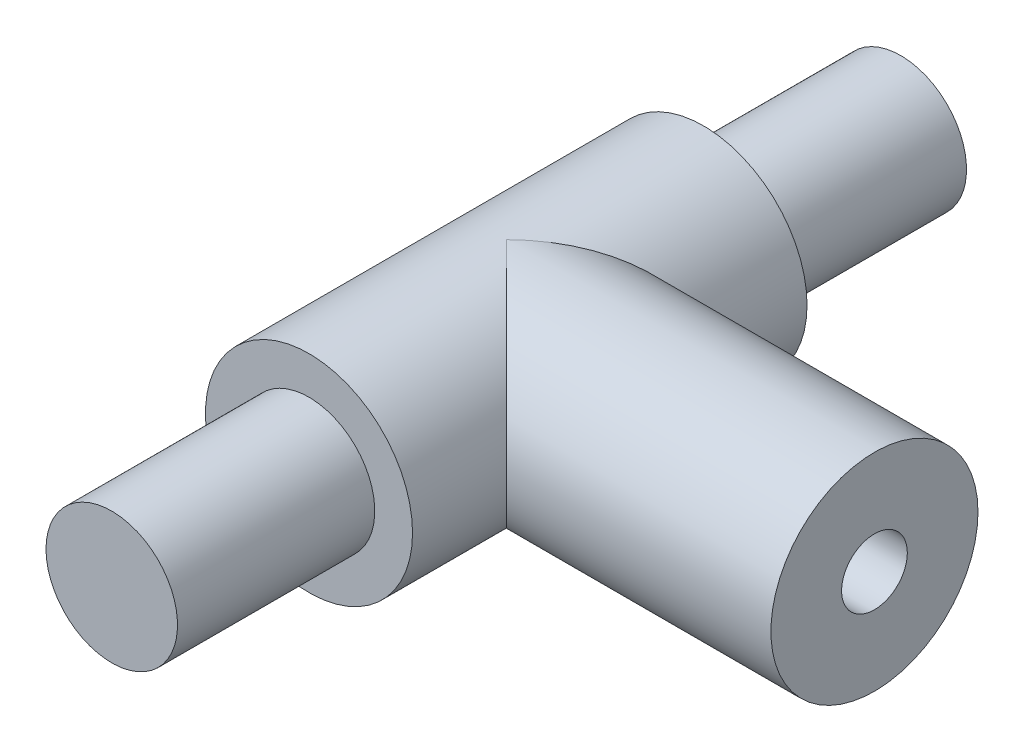
SolidWorks part; units mm, degrees
ref_plane "Front Plane" through (0, 0, 0) normal (0, 0, 1) x (1, 0, 0)
ref_plane "Top Plane" through (0, 0, 0) normal (0, 1, 0) x (1, 0, 0)
ref_plane "Right Plane" through (0, 0, 0) normal (1, 0, 0) x (0, 0, -1)
sketch "Sketch1" plane through (0, 0, 0) normal (0, 0, 1) x (1, 0, 0)
  circle A0 centre (0, 0) radius 5
  dimension "D1" = 10
extrude "Boss-Extrude1" add sketch "Sketch1" along normal mid plane 19.05
sketch "Sketch5" plane through (0, 0, 0) normal (0, 0, 1) x (1, 0, 0)
  circle A0 centre (0, 0) radius 3.175
  dimension "D1" = 6.35
extrude "Boss-Extrude4" add sketch "Sketch5" along normal mid plane 38.1
sketch "Sketch6" plane through (0, 0, 0) normal (1, 0, 0) x (0, 0, -1)
  circle A0 centre (0, 0) radius 5
  dimension "D1" = 10
extrude "Boss-Extrude5" add sketch "Sketch6" along normal blind 17.78
sketch "Sketch7" plane through (17.78, 0, 0) normal (1, 0, 0) x (0, 0, -1)
  circle A0 centre (0, 0) radius 1.5875
  dimension "D1" = 3.175
extrude "Cut-Extrude1" cut sketch "Sketch7" against normal blind 12.7
